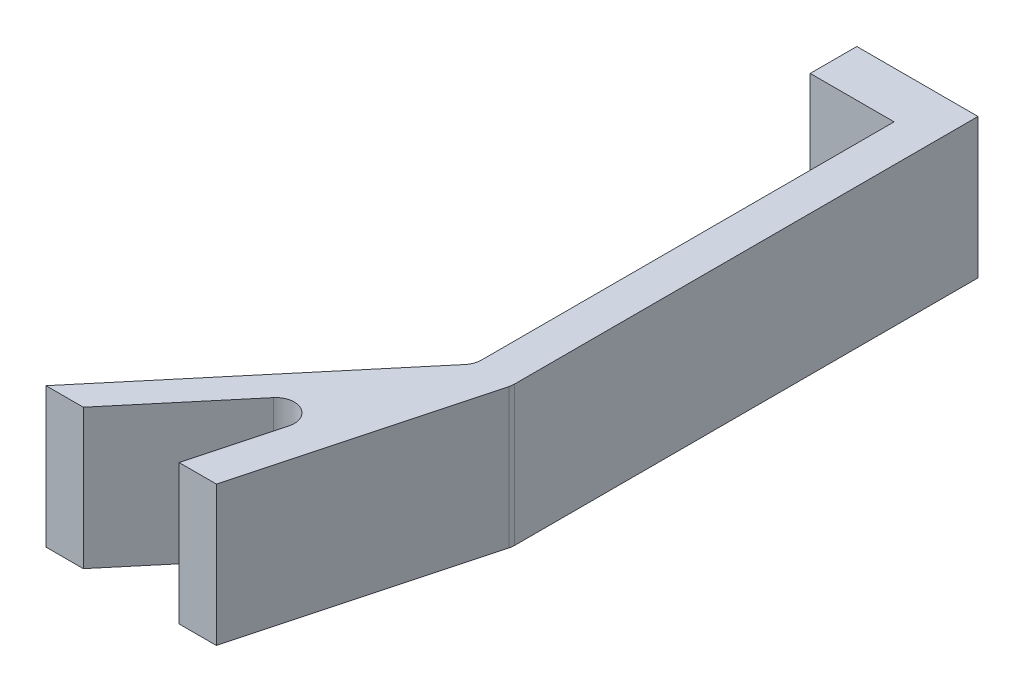
SolidWorks part; units mm, degrees
material "ABS PC"
ref_plane "Front Plane" through (0, 0, 0) normal (0, 0, 1) x (1, 0, 0)
ref_plane "Top Plane" through (0, 0, 0) normal (0, 1, 0) x (1, 0, 0)
ref_plane "Right Plane" through (0, 0, 0) normal (1, 0, 0) x (0, 0, -1)
sketch "Sketch1" plane through (0, 0, 0) normal (0, 1, 0) x (1, 0, 0)
  line L0 (0, 355.2663) -> (0, 0) construction
  line L1 (-486.7902, 0) -> (453.4144, 0) construction
  line L2 (0, 0) -> (-2, 0) construction
  line L3 (-2, 0.7279) -> (-2, 30)
  line L4 (0, 0) -> (2, 0) construction
  line L5 (2, 0.2633) -> (2, 30)
  line L6 (-2, 30) -> (2, 30) construction
  line L7 (0, 0) -> (-36.9122, -43.9902) construction
  line L8 (-2.4679, -0.5576) -> (-22.9775, -25)
  line L9 (0, -7.4641) -> (0, -25) construction
  line L10 (0, -25) -> (-52.3028, -25) construction
  line L11 (0, -7.4641) -> (0, -454.0905) construction
  line L12 (-22.9775, -25) -> (-18.9775, -25)
  line L17 (0, 0) -> (-6.6987, -25) construction
  line L18 (-6.2115, -15.7174) -> (-8.6987, -25)
  line L19 (1.9319, -0.2543) -> (-4.6987, -25)
  line L20 (-8.6987, -25) -> (-4.6987, -25)
  line L21 (-9.6754, -13.9142) -> (-18.9775, -25)
  line L22 (2, 30) -> (2, 50)
  line L23 (2, 50) -> (-11, 50)
  line L24 (-11, 50) -> (-11, 45)
  line L25 (-11, 45) -> (-2, 45)
  line L26 (-2, 45) -> (-2, 30)
  arc A0 (-2.4679, -0.5576) -> (-2, 0.7279) centre (-4, 0.7279) ccw
  arc A1 (1.9319, -0.2543) -> (2, 0.2633) centre (0, 0.2633) ccw
  arc A2 (-6.2115, -15.7174) -> (-9.6754, -13.9142) centre (-8.1433, -15.1998) ccw
  point P0 (0, 0)
  point P33 (-3.8766, -7.0034)
  dimension "D7" = 2
  dimension "D1" = 2
  dimension "D2" = 2
  dimension "D3" = 30
  dimension "D4" = 30
  dimension "D5" = 50
  dimension "D6" = 25
  dimension "D9" = 15
  dimension "D10" = 7.0034
  dimension "D11" = 3.8766
extrude "Boss-Extrude1" add sketch "Sketch1" along normal blind 15
sketch "Sketch3" plane through (0, 0, -50) normal (0, 0, -1) x (-1, 0, 0)
  line L0 (-2, 15) -> (11, 0) construction
  circle A0 centre (4.5, 7.5) radius 1.5
extrude "Cut-Extrude2" cut sketch "Sketch3" against normal blind 10
